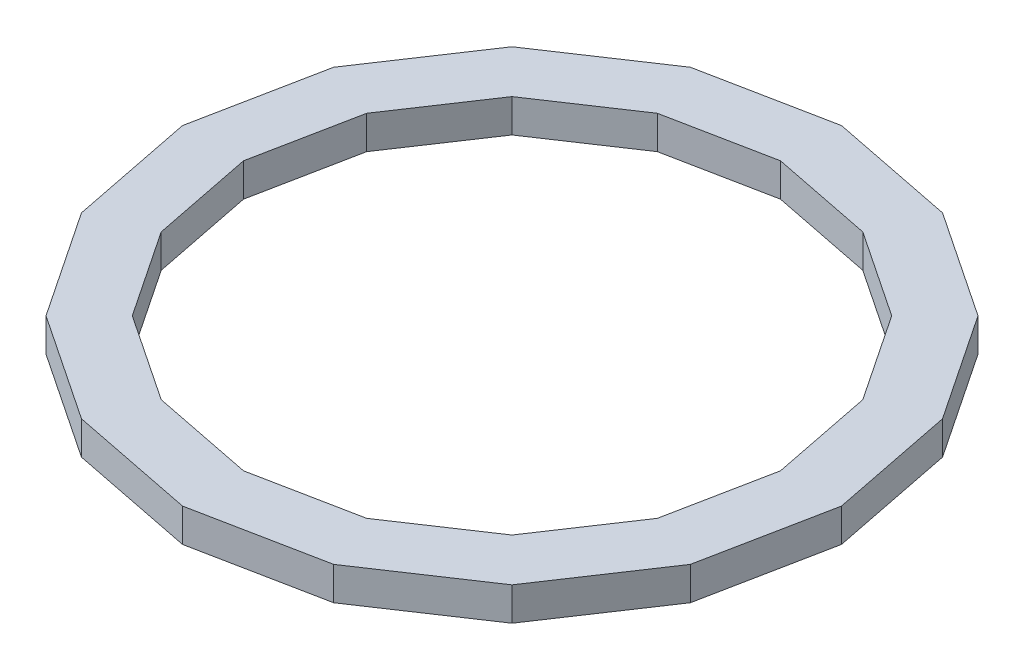
SolidWorks part; units mm, degrees
ref_plane "Front Plane" through (0, 0, 0) normal (0, 0, 1) x (1, 0, 0)
ref_plane "Top Plane" through (0, 0, 0) normal (0, 1, 0) x (1, 0, 0)
ref_plane "Right Plane" through (0, 0, 0) normal (1, 0, 0) x (0, 0, -1)
sketch "Sketch1" plane through (0, 0, 0) normal (0, 1, 0) x (1, 0, 0)
  line L1 (188.7844, 0) -> (174.414, 72.2446)
  line L2 (174.414, 72.2446) -> (133.4907, 133.4907)
  line L3 (133.4907, 133.4907) -> (72.2446, 174.414)
  line L4 (72.2446, 174.414) -> (0, 188.7844)
  line L5 (0, 188.7844) -> (-72.2446, 174.414)
  line L6 (-72.2446, 174.414) -> (-133.4907, 133.4907)
  line L7 (-133.4907, 133.4907) -> (-174.414, 72.2446)
  line L8 (-174.414, 72.2446) -> (-188.7844, 0)
  line L9 (-188.7844, 0) -> (-174.414, -72.2446)
  line L10 (-174.414, -72.2446) -> (-133.4907, -133.4907)
  line L11 (-133.4907, -133.4907) -> (-72.2446, -174.414)
  line L12 (-72.2446, -174.414) -> (0, -188.7844)
  line L13 (0, -188.7844) -> (72.2446, -174.414)
  line L14 (72.2446, -174.414) -> (133.4907, -133.4907)
  line L15 (133.4907, -133.4907) -> (174.414, -72.2446)
  line L16 (174.414, -72.2446) -> (188.7844, 0)
  line L17 (153.8226, 0) -> (142.1135, 58.8653)
  line L18 (142.1135, 58.8653) -> (108.769, 108.769)
  line L19 (108.769, 108.769) -> (58.8653, 142.1135)
  line L20 (58.8653, 142.1135) -> (0, 153.8226)
  line L21 (0, 153.8226) -> (-58.8653, 142.1135)
  line L22 (-58.8653, 142.1135) -> (-108.769, 108.769)
  line L23 (-108.769, 108.769) -> (-142.1135, 58.8653)
  line L24 (-142.1135, 58.8653) -> (-153.8226, 0)
  line L25 (-153.8226, 0) -> (-142.1135, -58.8653)
  line L26 (-142.1135, -58.8653) -> (-108.769, -108.769)
  line L27 (-108.769, -108.769) -> (-58.8653, -142.1135)
  line L28 (-58.8653, -142.1135) -> (0, -153.8226)
  line L29 (0, -153.8226) -> (58.8653, -142.1135)
  line L30 (58.8653, -142.1135) -> (108.769, -108.769)
  line L31 (108.769, -108.769) -> (142.1135, -58.8653)
  line L32 (142.1135, -58.8653) -> (153.8226, 0)
  circle A0 centre (0, 0) radius 185.1569 construction
  circle A1 centre (0, 0) radius 150.8669 construction
  dimension "D1" = 73.66
  dimension "D2" = 34.29
extrude "Boss-Extrude1" add sketch "Sketch1" along normal blind 19.05
